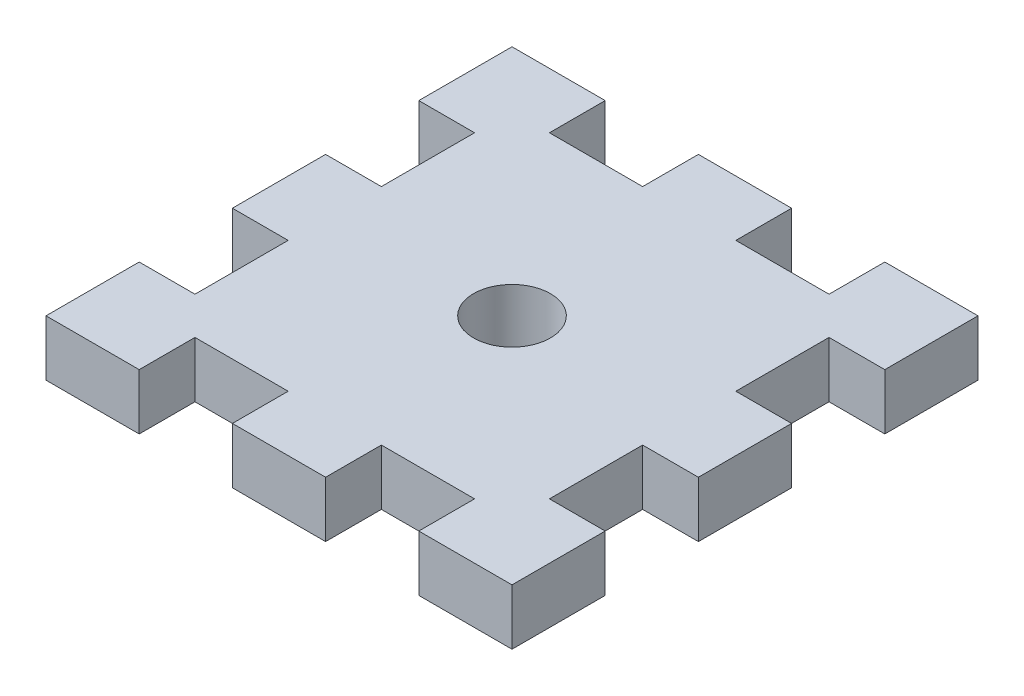
SolidWorks part; units mm, degrees
ref_plane "Front Plane" through (0, 0, 0) normal (0, 0, 1) x (1, 0, 0)
ref_plane "Top Plane" through (0, 0, 0) normal (0, 1, 0) x (1, 0, 0)
ref_plane "Right Plane" through (0, 0, 0) normal (1, 0, 0) x (0, 0, -1)
sketch "Sketch1" plane through (0, 0, 0) normal (0, 1, 0) x (1, 0, 0)
  line L0 (-19.05, 19.05) -> (19.05, 19.05)
  line L1 (-19.05, -19.05) -> (19.05, -19.05)
  line L2 (-19.05, -19.05) -> (-19.05, 19.05)
  line L3 (-19.05, 19.05) -> (19.05, 19.05)
  line L4 (19.05, -19.05) -> (19.05, 19.05)
  line L5 (-19.05, -19.05) -> (19.05, 19.05) construction
  line L6 (-19.05, 19.05) -> (19.05, -19.05) construction
  line L7 (-19.05, 19.05) -> (-14.4907, 19.05) construction
  line L8 (-19.05, 19.05) -> (-19.05, 11.43) construction
  line L9 (-19.05, 11.43) -> (-14.4907, 11.43) construction
  line L10 (-14.4907, 19.05) -> (-14.4907, 11.43) construction
  line L11 (-14.4907, 11.43) -> (-19.05, 11.43)
  line L12 (-14.4907, 11.43) -> (-14.4907, 3.81)
  line L13 (-14.4907, 3.81) -> (-19.05, 3.81)
  line L14 (-19.05, 11.43) -> (-19.05, 3.81)
  line L15 (-14.4907, 3.81) -> (-19.05, 3.81) construction
  line L16 (-14.4907, 3.81) -> (-14.4907, -3.81) construction
  line L17 (-14.4907, -3.81) -> (-19.05, -3.81) construction
  line L18 (-19.05, 3.81) -> (-19.05, -3.81) construction
  line L19 (-14.4907, -3.81) -> (-19.05, -3.81)
  line L20 (-14.4907, -3.81) -> (-14.4907, -11.43)
  line L21 (-14.4907, -11.43) -> (-19.05, -11.43)
  line L22 (-19.05, -3.81) -> (-19.05, -11.43)
  line L23 (-14.4907, -11.43) -> (-19.05, -11.43) construction
  line L24 (-14.4907, -11.43) -> (-14.4907, -19.05) construction
  line L25 (-14.4907, -19.05) -> (-19.05, -19.05) construction
  line L26 (-19.05, -11.43) -> (-19.05, -19.05) construction
  line L27 (11.43, 14.4907) -> (11.43, 19.05)
  line L28 (11.43, 14.4907) -> (3.81, 14.4907)
  line L29 (3.81, 14.4907) -> (3.81, 19.05)
  line L30 (11.43, 19.05) -> (3.81, 19.05)
  line L31 (-3.81, 14.4907) -> (-3.81, 19.05)
  line L32 (-3.81, 14.4907) -> (-11.43, 14.4907)
  line L33 (-11.43, 14.4907) -> (-11.43, 19.05)
  line L34 (-3.81, 19.05) -> (-11.43, 19.05)
  line L35 (19.05, 19.05) -> (19.05, 14.4907) construction
  line L36 (19.05, 19.05) -> (11.43, 19.05) construction
  line L37 (11.43, 19.05) -> (11.43, 14.4907) construction
  line L38 (19.05, 14.4907) -> (11.43, 14.4907) construction
  line L39 (3.81, 14.4907) -> (3.81, 19.05) construction
  line L40 (3.81, 14.4907) -> (-3.81, 14.4907) construction
  line L41 (-3.81, 14.4907) -> (-3.81, 19.05) construction
  line L42 (3.81, 19.05) -> (-3.81, 19.05) construction
  line L43 (-11.43, 14.4907) -> (-11.43, 19.05) construction
  line L44 (-11.43, 14.4907) -> (-19.05, 14.4907) construction
  line L45 (-19.05, 14.4907) -> (-19.05, 19.05) construction
  line L46 (-11.43, 19.05) -> (-19.05, 19.05) construction
  line L47 (19.05, 19.05) -> (19.05, -19.05)
  line L48 (14.4907, -11.43) -> (19.05, -11.43)
  line L49 (14.4907, -11.43) -> (14.4907, -3.81)
  line L50 (14.4907, -3.81) -> (19.05, -3.81)
  line L51 (19.05, -11.43) -> (19.05, -3.81)
  line L52 (14.4907, 3.81) -> (19.05, 3.81)
  line L53 (14.4907, 3.81) -> (14.4907, 11.43)
  line L54 (14.4907, 11.43) -> (19.05, 11.43)
  line L55 (19.05, 3.81) -> (19.05, 11.43)
  line L56 (19.05, -19.05) -> (14.4907, -19.05) construction
  line L57 (19.05, -19.05) -> (19.05, -11.43) construction
  line L58 (19.05, -11.43) -> (14.4907, -11.43) construction
  line L59 (14.4907, -19.05) -> (14.4907, -11.43) construction
  line L60 (14.4907, -3.81) -> (19.05, -3.81) construction
  line L61 (14.4907, -3.81) -> (14.4907, 3.81) construction
  line L62 (14.4907, 3.81) -> (19.05, 3.81) construction
  line L63 (19.05, -3.81) -> (19.05, 3.81) construction
  line L64 (14.4907, 11.43) -> (19.05, 11.43) construction
  line L65 (14.4907, 11.43) -> (14.4907, 19.05) construction
  line L66 (14.4907, 19.05) -> (19.05, 19.05) construction
  line L67 (19.05, 11.43) -> (19.05, 19.05) construction
  line L68 (19.05, -19.05) -> (-19.05, -19.05)
  line L69 (-11.43, -14.4907) -> (-11.43, -19.05)
  line L70 (-11.43, -14.4907) -> (-3.81, -14.4907)
  line L71 (-3.81, -14.4907) -> (-3.81, -19.05)
  line L72 (-11.43, -19.05) -> (-3.81, -19.05)
  line L73 (3.81, -14.4907) -> (3.81, -19.05)
  line L74 (3.81, -14.4907) -> (11.43, -14.4907)
  line L75 (11.43, -14.4907) -> (11.43, -19.05)
  line L76 (3.81, -19.05) -> (11.43, -19.05)
  line L77 (-19.05, -19.05) -> (-19.05, -14.4907) construction
  line L78 (-19.05, -19.05) -> (-11.43, -19.05) construction
  line L79 (-11.43, -19.05) -> (-11.43, -14.4907) construction
  line L80 (-19.05, -14.4907) -> (-11.43, -14.4907) construction
  line L81 (-3.81, -14.4907) -> (-3.81, -19.05) construction
  line L82 (-3.81, -14.4907) -> (3.81, -14.4907) construction
  line L83 (3.81, -14.4907) -> (3.81, -19.05) construction
  line L84 (-3.81, -19.05) -> (3.81, -19.05) construction
  line L85 (11.43, -14.4907) -> (11.43, -19.05) construction
  line L86 (11.43, -14.4907) -> (19.05, -14.4907) construction
  line L87 (19.05, -14.4907) -> (19.05, -19.05) construction
  line L88 (11.43, -19.05) -> (19.05, -19.05) construction
  circle A0 centre (0, 0) radius 3.1433
  point P0 (0, 0)
  point P57 (0, 0)
  dimension "D2" = 6.2865
  dimension "D1" = 38.1
  dimension "D3" = 4.5593
extrude "Boss-Extrude1" add sketch "Sketch1" along normal blind 4.5593 contours L74 L75 L1 L4 L48 L49 L50 L52 L53 L54 L3 L27 L28 L29 L31 L32 L33 L0 L2 L11 L12 L13 L19 L20 L21 L69 L70 L71 L73 A0
equation "\"material_width\" = 0.1795"
equation "\"head_height\" = 2.0"
equation "\"neck_height\" = \"max32_width\""
equation "\"washer_height\" = 0.1"
equation "\"wall_length\" = 3.5"
equation "\"wall_height\" = 1.5"
equation "\"extra_space\" = 0.25"
equation "\"arc_radius\" = \"wall_length\" + \"washer_height\" + \"neck_height\" + (\"head_height\"/2)"
equation "\"arc_wall_height\" = \"arc_radius\" + \"wall_length\" + \"extra_space\""
equation "\"foot_length\" = 1.0"
equation "\"peg_diameter\" = 0.2475"
equation "\"barring_diameter\" = 0.8657"
equation "\"D1@Sketch1\"=\"wall_height\""
equation "\"D2@Sketch1\"=\"peg_diameter\""
equation "\"D3@Sketch1\"=\"material_width\""
equation "\"D1@Boss-Extrude1\"=\"material_width\""
